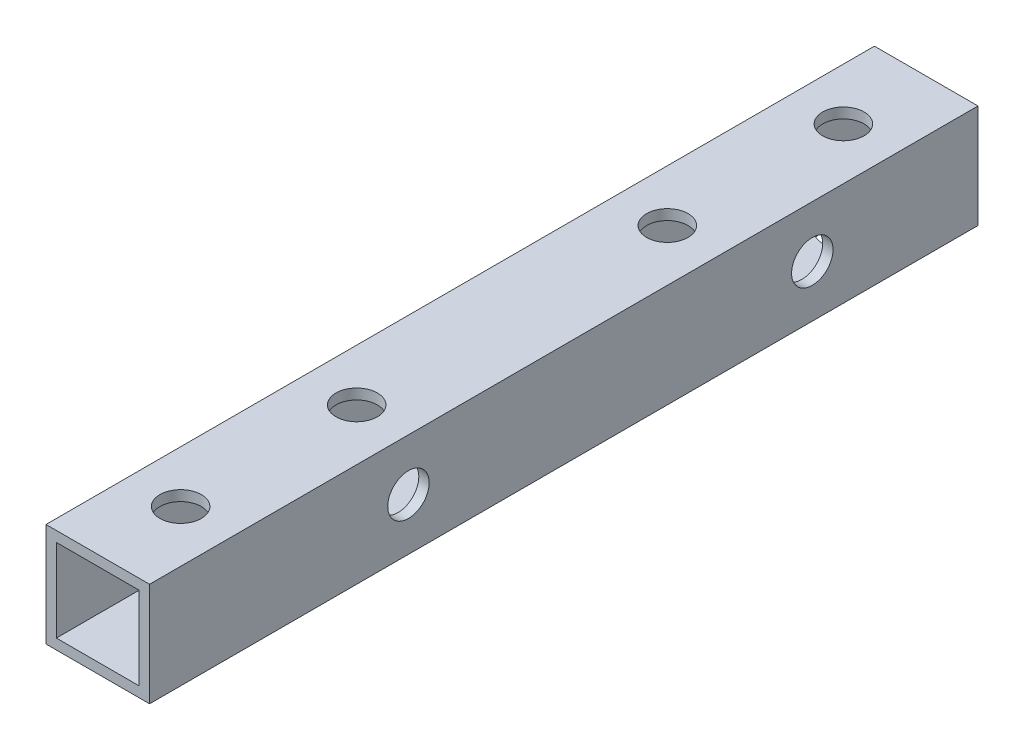
SolidWorks part; units mm, degrees
ref_plane "前视基准面" through (0, 0, 0) normal (0, 0, 1) x (1, 0, 0)
ref_plane "上视基准面" through (0, 0, 0) normal (0, 1, 0) x (1, 0, 0)
ref_plane "右视基准面" through (0, 0, 0) normal (1, 0, 0) x (0, 0, -1)
sketch "草图1" plane through (0, 0, 0) normal (0, 0, 1) x (1, 0, 0)
  line L0 (0, 0) -> (0, 10)
  line L1 (0, 10) -> (10, 10)
  line L2 (10, 10) -> (10, 0)
  line L3 (10, 0) -> (0, 0)
  line L4 (1, 9) -> (9, 9)
  line L5 (9, 9) -> (9, 1)
  line L6 (9, 1) -> (1, 1)
  line L7 (1, 1) -> (1, 9)
  point P9 (0, 0)
  point P10 (0, 0)
  dimension "D1" = 10
  dimension "D2" = 10
  dimension "D3" = 1
  dimension "D4" = 1
  dimension "D5" = 1
  dimension "D6" = 1
extrude "凸台-拉伸2" add sketch "草图1" along normal blind 80
sketch "草图2" plane through (0, 10, 0) normal (0, 1, 0) x (1, 0, 0)
  line L0 (10, -80) -> (0, -80) construction
  line L1 (0, -80) -> (0, 0) construction
  line L2 (10, 0) -> (0, 0) construction
  circle A0 centre (5, -72) radius 2
  circle A1 centre (5, -8) radius 2
  dimension "D1" = 8
  dimension "D2" = 5
  dimension "D3" = 8
extrude "切除-拉伸1" cut sketch "草图2" against normal blind 70
sketch "草图3" plane through (0, 0, 0) normal (0, -1, 0) x (1, 0, 0)
  line L0 (10, 80) -> (10, 0) construction
  line L1 (0, 0) -> (10, 0) construction
  circle A0 centre (5, 25) radius 2
  dimension "D1" = 5
  dimension "D2" = 25
extrude "切除-拉伸2" cut sketch "草图3" against normal blind 104
sketch "草图4" plane through (0, 0, 0) normal (0, -1, 0) x (1, 0, 0)
  line L0 (10, 80) -> (10, 0) construction
  line L1 (0, 0) -> (10, 0) construction
  circle A0 centre (5, 55) radius 2
  dimension "D1" = 5
  dimension "D2" = 55
extrude "切除-拉伸3" cut sketch "草图4" against normal blind 104
sketch "草图5" plane through (10, 0, 0) normal (1, 0, 0) x (0, 0, -1)
  line L0 (-80, 10) -> (0, 10) construction
  line L1 (0, 0) -> (0, 10) construction
  circle A0 centre (-16, 5) radius 2
  dimension "D1" = 5
  dimension "D2" = 16
extrude "切除-拉伸4" cut sketch "草图5" against normal blind 100
sketch "草图6" plane through (0, 0, 0) normal (-1, 0, 0) x (0, 0, 1)
  line L0 (80, 10) -> (0, 10) construction
  line L1 (80, 10) -> (80, 0) construction
  circle A0 centre (55, 5) radius 2
  dimension "D1" = 5
  dimension "D2" = 25
extrude "切除-拉伸5" cut sketch "草图6" against normal blind 10 contours A0
